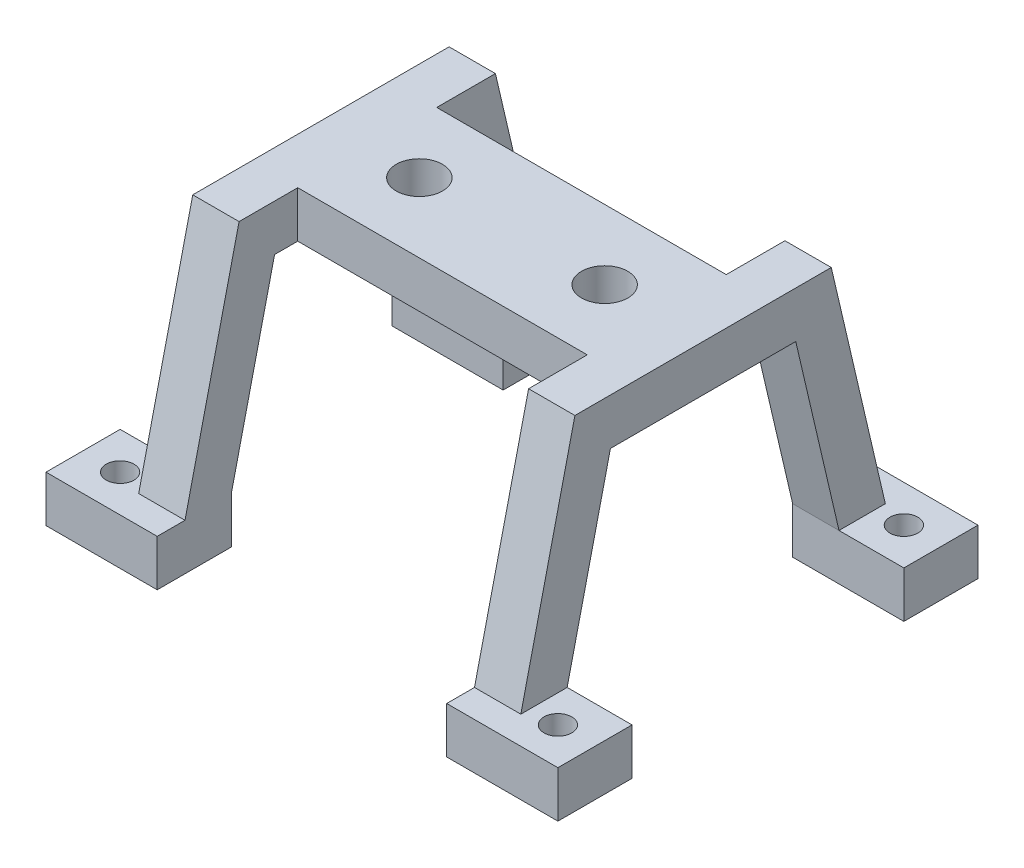
SolidWorks part; units mm, degrees
ref_plane "前视基准面" through (0, 0, 0) normal (0, 0, 1) x (1, 0, 0)
ref_plane "上视基准面" through (0, 0, 0) normal (0, 1, 0) x (1, 0, 0)
ref_plane "右视基准面" through (0, 0, 0) normal (1, 0, 0) x (0, 0, -1)
sketch "草图1" plane through (0, 0, 0) normal (0, 1, 0) x (1, 0, 0)
  line L0 (-23.622, 18.669) -> (-23.622, -18.669) construction
  line L1 (-23.622, 18.669) -> (23.622, 18.669) construction
  line L3 (-27.622, -14.669) -> (-15.622, -14.669)
  line L4 (-27.622, -14.669) -> (-27.622, -22.669)
  line L5 (-27.622, -22.669) -> (-15.622, -22.669)
  line L6 (-15.622, -14.669) -> (-15.622, -22.669)
  circle A0 centre (-23.622, -18.669) radius 1.5
  circle A1 centre (-23.622, 18.669) radius 1.5 construction
  circle A2 centre (23.622, -18.669) radius 1.5 construction
  circle A3 centre (23.622, 18.669) radius 1.5 construction
  point P8 (-23.622, 0)
  point P9 (-27.622, -18.669)
  point P11 (0, 18.669)
  dimension "D1" = 37.338
  dimension "D3" = 3
  dimension "D2" = 47.244
  dimension "D4" = 8
  dimension "D5" = 8
  dimension "D6" = 12
extrude "凸台-拉伸1" add sketch "草图1" along normal blind 5
sketch "草图2" plane through (-15.622, 0, 0) normal (1, 0, 0) x (0, 0, -1)
  line L0 (-10, 25) -> (-14.669, 5)
  line L1 (-10, 25) -> (0, 25)
  line L2 (0, 25) -> (0, 30)
  line L3 (0, 30) -> (-13.8327, 30)
  line L4 (-13.8327, 30) -> (-19.669, 5)
  line L6 (-22.669, 5) -> (-14.669, 5) construction
  line L7 (-19.669, 5) -> (-19.669, 0)
  line L8 (-22.669, 0) -> (-14.669, 0) construction
  line L9 (-19.669, 0) -> (-14.669, 0)
  line L10 (-22.669, 0) -> (-14.669, 0)
  line L11 (-14.669, 0) -> (-14.669, 5)
  line L12 (-14.669, 5) -> (-22.669, 5)
  line L13 (-22.669, 5) -> (-22.669, 0)
  line L15 (-14.669, 0) -> (-14.669, 5)
  dimension "D1" = 10
  dimension "D2" = 5
  dimension "D3" = 20
  dimension "D6" = 5
  dimension "D4" = 0
extrude "凸台-拉伸2" add sketch "草图2" against normal blind 5
mirror "镜向4" about plane through (0, 0, 0) normal (0, 0, 1) of "凸台-拉伸2", "凸台-拉伸1"
sketch "草图3" plane through (0, 30, 0) normal (0, 1, 0) x (1, 0, 0)
  line L0 (-15.622, 13.8327) -> (-15.622, -13.8327) construction
  line L1 (-15.622, 7.5) -> (0, 7.5)
  line L2 (-15.622, 7.5) -> (-15.622, -7.5)
  line L3 (-15.622, -7.5) -> (0, -7.5)
  line L4 (0, 7.5) -> (0, -7.5)
  circle A0 centre (-10, 0) radius 2.5
  point P6 (0, 0)
  dimension "D2" = 5
  dimension "D1" = 15
  dimension "D3" = 10
extrude "凸台-拉伸3" add sketch "草图3" against normal blind 5
mirror "镜向5" about plane through (0, 0, 0) normal (1, 0, 0) of "凸台-拉伸2", "镜向4", "凸台-拉伸3", "凸台-拉伸1"
